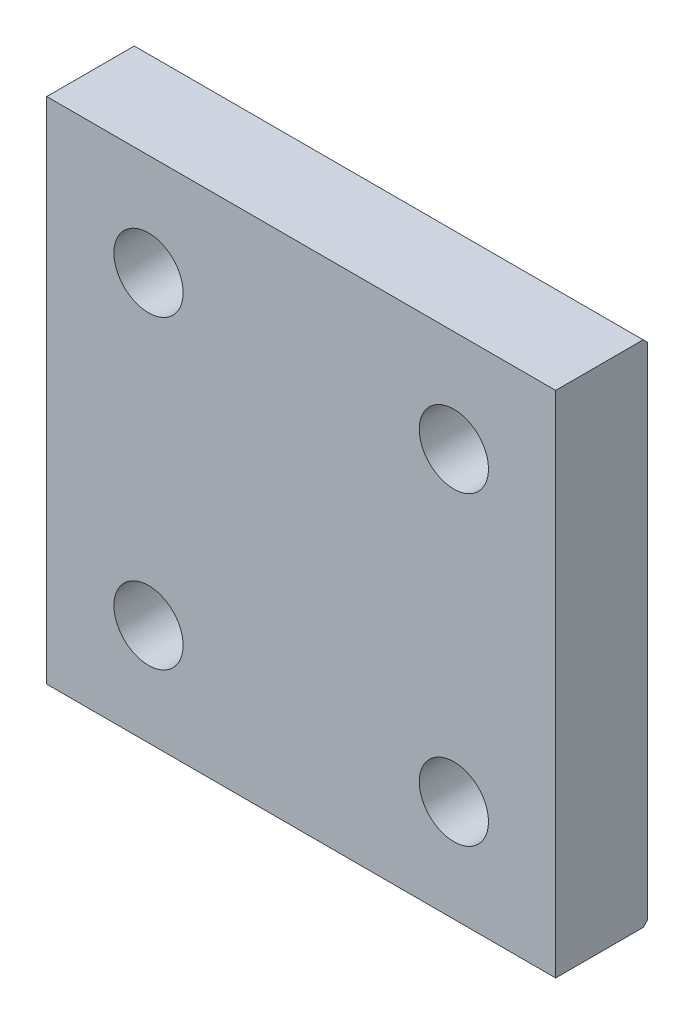
SolidWorks part; units mm, degrees
ref_plane "前基準面" through (0, 0, 0) normal (0, 0, 1) x (1, 0, 0)
ref_plane "上基準面" through (0, 0, 0) normal (0, 1, 0) x (1, 0, 0)
ref_plane "右基準面" through (0, 0, 0) normal (1, 0, 0) x (0, 0, -1)
sketch "草圖1" plane through (0, 0, 0) normal (0, 0, 1) x (1, 0, 0)
  line L1 (12.5, -12.5) -> (-12.5, -12.5)
  line L2 (12.5, -12.5) -> (12.5, 12.5)
  line L3 (12.5, 12.5) -> (-12.5, 12.5)
  line L4 (-12.5, -12.5) -> (-12.5, 12.5)
  line L5 (12.5, -12.5) -> (-12.5, 12.5) construction
  line L6 (12.5, 12.5) -> (-12.5, -12.5) construction
  point P0 (0, 0)
  dimension "D1" = 25
  dimension "D2" = 25
extrude "填料-伸長1" add sketch "草圖1" along normal blind 4.5
sketch "草圖2" plane through (0, 0, 0) normal (0, 0, -1) x (-1, 0, 0)
  line L1 (-7.5, -7.5) -> (7.5, -7.5) construction
  line L2 (-7.5, -7.5) -> (-7.5, 7.5) construction
  line L3 (-7.5, 7.5) -> (7.5, 7.5) construction
  line L4 (7.5, -7.5) -> (7.5, 7.5) construction
  line L5 (-7.5, -7.5) -> (7.5, 7.5) construction
  line L6 (-7.5, 7.5) -> (7.5, -7.5) construction
  circle A0 centre (-7.5, 7.5) radius 1.7
  point P0 (0, 0)
  dimension "D3" = 3.4
  dimension "D1" = 15
  dimension "D2" = 15
extrude "除料-伸長1" cut sketch "草圖2" against normal through all
pattern_linear "直線複製排列1" count 2 spacing 15 along (-1, 0, 0) count 2 spacing 15 along (0, -1, 0) of "除料-伸長1"
chamfer "導角1" distance 0.2 angle 45 6 edges at (0, -12.5, 0) (5.8, -7.5, 0) (-9.2, -7.5, 0) (-9.2, 7.5, 0) (5.8, 7.5, 0) (0, 12.5, 0)
